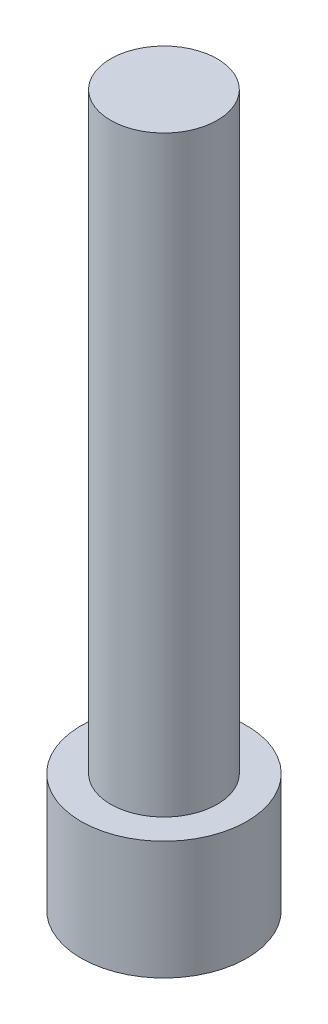
SolidWorks part; units mm, degrees
ref_plane "Płaszczyzna przednia" through (0, 0, 0) normal (0, 0, 1) x (1, 0, 0)
ref_plane "Płaszczyzna górna" through (0, 0, 0) normal (0, 1, 0) x (1, 0, 0)
ref_plane "Płaszczyzna prawa" through (0, 0, 0) normal (1, 0, 0) x (0, 0, -1)
sketch "Szkic1" plane through (0, 0, 0) normal (0, 1, 0) x (1, 0, 0)
  circle A0 centre (0, 0) radius 7
  dimension "D1" = 14
extrude "Dodanie-wyciągnięcie1" add sketch "Szkic1" along normal blind 10
sketch "Szkic2" plane through (0, 10, 0) normal (0, 1, 0) x (1, 0, 0)
  circle A0 centre (0, 0) radius 4.5
  dimension "D1" = 9
extrude "Dodanie-wyciągnięcie2" add sketch "Szkic2" along normal blind 50
sketch "Szkic3" plane through (0, 0, 0) normal (0, -1, 0) x (1, 0, 0)
  line L1 (0, -3.4641) -> (3, -1.7321)
  line L2 (3, -1.7321) -> (3, 1.7321)
  line L3 (3, 1.7321) -> (0, 3.4641)
  line L4 (0, 3.4641) -> (-3, 1.7321)
  line L5 (-3, 1.7321) -> (-3, -1.7321)
  line L6 (-3, -1.7321) -> (0, -3.4641)
  circle A0 centre (0, 0) radius 3 construction
  point P1 (0, 0)
  dimension "D1" = 6
extrude "Wytnij-wyciągnięcie1" cut sketch "Szkic3" against normal blind 5
